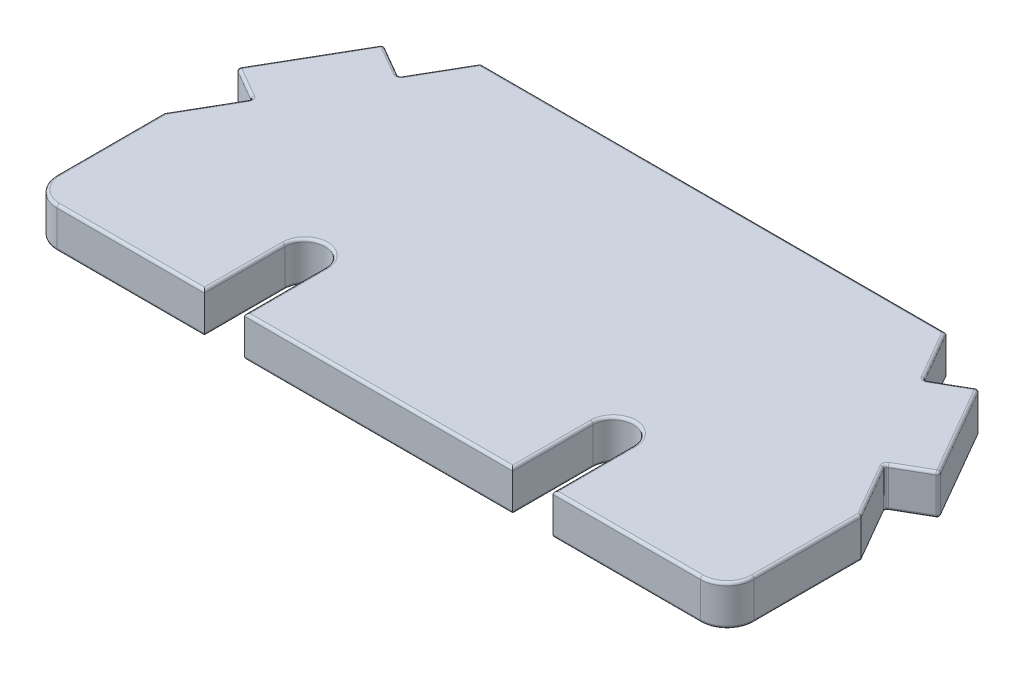
SolidWorks part; units mm, degrees
ref_plane "Front Plane" through (0, 0, 0) normal (0, 0, 1) x (1, 0, 0)
ref_plane "Top Plane" through (0, 0, 0) normal (0, 1, 0) x (1, 0, 0)
ref_plane "Right Plane" through (0, 0, 0) normal (1, 0, 0) x (0, 0, -1)
sketch "Sketch1" plane through (0, 0, 0) normal (0, 1, 0) x (1, 0, 0)
  line L0 (0, 0) -> (0, 28) construction
  line L1 (10, 0) -> (-10, 0)
  line L2 (-10, 0) -> (-10, 6)
  line L3 (19.6077, 21.0718) -> (17.3577, 24.9689)
  line L4 (-13, 6) -> (-13, 0)
  line L5 (-13, 0) -> (-24, 0)
  line L6 (-26, 2) -> (-26, 10)
  line L7 (-26, 10) -> (-23.6077, 14.1436)
  line L8 (-23.6077, 14.1436) -> (-26.2058, 15.6436)
  line L9 (-26.2058, 15.6436) -> (-22.2058, 22.5718)
  line L10 (-22.2058, 22.5718) -> (-19.6077, 21.0718)
  line L11 (-19.6077, 21.0718) -> (-17.3577, 24.9689)
  line L13 (22.2058, 22.5718) -> (19.6077, 21.0718)
  line L14 (26.2058, 15.6436) -> (22.2058, 22.5718)
  line L15 (23.6077, 14.1436) -> (26.2058, 15.6436)
  line L16 (26, 10) -> (23.6077, 14.1436)
  line L17 (26, 2) -> (26, 10)
  line L18 (13, 0) -> (24, 0)
  line L19 (13, 6) -> (13, 0)
  line L20 (10, 0) -> (10, 6)
  line L21 (-17.3577, 24.9689) -> (17.3577, 24.9689)
  arc A0 (-10, 6) -> (-13, 6) centre (-11.5, 6) ccw
  arc A1 (10, 6) -> (13, 6) centre (11.5, 6) cw
  arc A2 (-24, 0) -> (-26, 2) centre (-24, 2) cw
  arc A3 (26, 2) -> (24, 0) centre (24, 2) cw
  point P29 (-26, 0)
  point P32 (26, 0)
  dimension "D5" = 1.5
  dimension "D12" = 2
  dimension "D1" = 28
  dimension "D2" = 3
  dimension "D3" = 10
  dimension "D4" = 6
  dimension "D6" = 26
  dimension "D7" = 10
  dimension "D8" = 30
  dimension "D9" = 8
  dimension "D10" = 3
  dimension "D11" = 4.5
  dimension "D13" = 21.0718
extrude "Boss-Extrude1" add sketch "Sketch1" along normal blind 3
ref_plane "Plane1" through (0, 0, -6) normal (0, 0, 1) x (0, -1, 0)
fillet "Fillet1" radius 0.2 56 edges at (22.2058, 1.5, -22.5718) (-26, 0, -6) (-18.5, 0, 0) (-13, 0, -3) (-11.5, 0, -7.5) (-10, 0, -3) (0, 0, 0) (10, 0, -3) (11.5, 0, -7.5) (13, 0, -3) (18.5, 0, 0) (26, 0, -6) (24.8038, 0, -12.0718) (24.9067, 0, -14.8936) (24.2058, 0, -19.1077) (20.9067, 0, -21.8218) (-18.4827, 0, -23.0204) (-20.9067, 0, -21.8218) (-24.2058, 0, -19.1077) (-24.9067, 0, -14.8936) (-24.8038, 0, -12.0718) (-24.9067, 3, -14.8936) (-24.2058, 3, -19.1077) (-20.9067, 3, -21.8218) (-18.4827, 3, -23.0204) (20.9067, 3, -21.8218) (24.2058, 3, -19.1077) (24.9067, 3, -14.8936) (24.8038, 3, -12.0718) (26, 3, -6) (18.5, 3, 0) (13, 3, -3) (11.5, 3, -7.5) (10, 3, -3) (0, 3, 0) (-10, 3, -3) (-11.5, 3, -7.5) (-13, 3, -3) (-18.5, 3, 0) (-26, 3, -6) (-24.8038, 3, -12.0718) (23.6077, 1.5, -14.1436) (26.2058, 1.5, -15.6436) (-23.6077, 1.5, -14.1436) (-26.2058, 1.5, -15.6436) (-19.6077, 1.5, -21.0718) (-22.2058, 1.5, -22.5718) (-25.4142, 0, -0.5858) (25.4142, 0, -0.5858) (25.4142, 3, -0.5858) (-25.4142, 3, -0.5858) (19.6077, 1.5, -21.0718) (18.4827, 0, -23.0204) (0, 0, -24.9689) (0, 3, -24.9689) (18.4827, 3, -23.0204)
